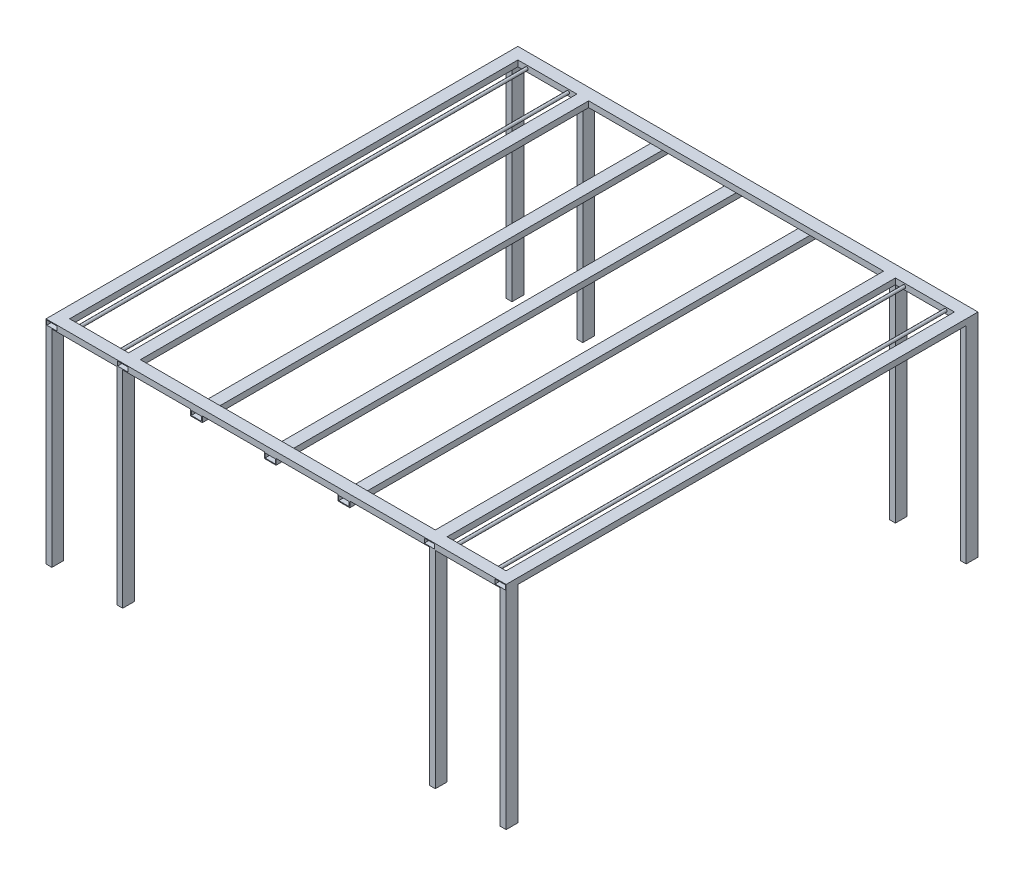
SolidWorks part; units mm, degrees
ref_plane "Front Plane" through (0, 0, 0) normal (0, 0, 1) x (1, 0, 0)
ref_plane "Top Plane" through (0, 0, 0) normal (0, 1, 0) x (1, 0, 0)
ref_plane "Right Plane" through (0, 0, 0) normal (1, 0, 0) x (0, 0, -1)
sketch "Sketch1" plane through (0, 0, 0) normal (0, 0, 1) x (1, 0, 0)
  line L0 (-17.5, 7.5) -> (17.5, 7.5)
  line L1 (-20, 10) -> (20, 10)
  line L2 (-20, 10) -> (-20, -10)
  line L3 (-20, -10) -> (20, -10)
  line L4 (20, 10) -> (20, -10)
  line L5 (-20, 10) -> (20, -10) construction
  line L6 (-20, -10) -> (20, 10) construction
  line L7 (17.5, 7.5) -> (17.5, -7.5)
  line L8 (-17.5, -7.5) -> (17.5, -7.5)
  line L9 (-17.5, 7.5) -> (-17.5, -7.5)
  point P0 (0, 0)
  dimension "D1" = 40
  dimension "D2" = 20
  dimension "D3" = 2.5
extrude "Boss-Extrude1" add sketch "Sketch1" along normal blind 1600
sketch "Sketch2" plane through (20, 0, 0) normal (1, 0, 0) x (0, 0, -1)
  line L0 (-1600, -10) -> (0, -10) construction
  line L1 (-1600, 10) -> (-1560, 10)
  line L2 (-1600, 10) -> (-1600, -10)
  line L3 (-1600, -10) -> (-1560, -10)
  line L4 (-1560, 10) -> (-1560, -10)
  line L5 (-1597.5, 7.5) -> (-1562.5, 7.5)
  line L6 (-1562.5, 7.5) -> (-1562.5, -7.5)
  line L7 (-1597.5, -7.5) -> (-1562.5, -7.5)
  line L8 (-1597.5, 7.5) -> (-1597.5, -7.5)
  line L9 (-2.5, 7.5) -> (-37.5, 7.5)
  line L10 (0, 10) -> (-40, 10)
  line L11 (0, 10) -> (0, -10)
  line L12 (0, -10) -> (-40, -10)
  line L13 (-40, 10) -> (-40, -10)
  line L14 (-37.5, 7.5) -> (-37.5, -7.5)
  line L15 (-2.5, -7.5) -> (-37.5, -7.5)
  line L16 (-2.5, 7.5) -> (-2.5, -7.5)
  dimension "D1" = 2.5
  dimension "D2" = 2.5
  dimension "D3" = 40
extrude "Boss-Extrude3" add sketch "Sketch2" along normal blind 1000
sketch "Sketch3" plane through (0, 0, 1600) normal (0, 0, 1) x (1, 0, 0)
  line L0 (1022.5, 7.5) -> (1057.5, 7.5)
  line L1 (1020, 10) -> (1060, 10)
  line L2 (1020, 10) -> (1020, -10)
  line L3 (1020, -10) -> (1060, -10)
  line L4 (1060, 10) -> (1060, -10)
  line L5 (1057.5, 7.5) -> (1057.5, -7.5)
  line L6 (1022.5, -7.5) -> (1057.5, -7.5)
  line L7 (1022.5, 7.5) -> (1022.5, -7.5)
  dimension "D1" = 40
  dimension "D2" = 2.5
extrude "Boss-Extrude4" add sketch "Sketch3" against normal blind 1600
sketch "Sketch4" plane through (0, -10, 0) normal (0, -1, 0) x (1, 0, 0)
  line L0 (1057.5, 1597.5) -> (1057.5, 1562.5)
  line L1 (1060, 1600) -> (1040, 1600)
  line L2 (1060, 1600) -> (1060, 1560)
  line L3 (1060, 1560) -> (1040, 1560)
  line L4 (1040, 1600) -> (1040, 1560)
  line L5 (1060, 0) -> (1040, 0)
  line L6 (1060, 0) -> (1060, 40)
  line L7 (1060, 40) -> (1040, 40)
  line L8 (1040, 0) -> (1040, 40)
  line L9 (-20, 0) -> (0, 0)
  line L10 (-20, 0) -> (-20, 40)
  line L11 (-20, 40) -> (0, 40)
  line L12 (0, 0) -> (0, 40)
  line L13 (-20, 1600) -> (0, 1600)
  line L14 (-20, 1600) -> (-20, 1560)
  line L15 (-20, 1560) -> (0, 1560)
  line L16 (0, 1600) -> (0, 1560)
  line L17 (1057.5, 1562.5) -> (1042.5, 1562.5)
  line L18 (1042.5, 1597.5) -> (1042.5, 1562.5)
  line L19 (1057.5, 1597.5) -> (1042.5, 1597.5)
  line L20 (1057.5, 2.5) -> (1057.5, 37.5)
  line L21 (1057.5, 37.5) -> (1042.5, 37.5)
  line L22 (1042.5, 2.5) -> (1042.5, 37.5)
  line L23 (1057.5, 2.5) -> (1042.5, 2.5)
  line L24 (-17.5, 2.5) -> (-17.5, 37.5)
  line L25 (-17.5, 37.5) -> (-2.5, 37.5)
  line L26 (-2.5, 2.5) -> (-2.5, 37.5)
  line L27 (-17.5, 2.5) -> (-2.5, 2.5)
  line L28 (-17.5, 1597.5) -> (-17.5, 1562.5)
  line L29 (-17.5, 1562.5) -> (-2.5, 1562.5)
  line L30 (-2.5, 1597.5) -> (-2.5, 1562.5)
  line L31 (-17.5, 1597.5) -> (-2.5, 1597.5)
  dimension "D1" = 20
  dimension "D2" = 20
  dimension "D3" = 20
  dimension "D4" = 20
  dimension "D6" = 40
  dimension "40" = 40
  dimension "D5" = 2.5
extrude "Boss-Extrude5" add sketch "Sketch4" along normal blind 700
sketch "Sketch5" plane through (0, 0, 1600) normal (0, 0, 1) x (1, 0, 0)
  line L0 (0, -10) -> (1040, -10) construction
  line L1 (230, -10) -> (270, -10)
  line L2 (230, -10) -> (230, -30)
  line L3 (230, -30) -> (270, -30)
  line L4 (270, -10) -> (270, -30)
  line L5 (0, -710) -> (0, -10) construction
  line L6 (480, -10) -> (520, -10)
  line L7 (480, -10) -> (480, -30)
  line L8 (480, -30) -> (520, -30)
  line L9 (520, -10) -> (520, -30)
  line L10 (730, -10) -> (770, -10)
  line L11 (730, -10) -> (730, -30)
  line L12 (730, -30) -> (770, -30)
  line L13 (770, -10) -> (770, -30)
  line L14 (232.5, -27.5) -> (267.5, -27.5)
  line L15 (267.5, -12.5) -> (267.5, -27.5)
  line L16 (232.5, -12.5) -> (267.5, -12.5)
  line L17 (232.5, -12.5) -> (232.5, -27.5)
  line L18 (482.5, -27.5) -> (517.5, -27.5)
  line L19 (517.5, -12.5) -> (517.5, -27.5)
  line L20 (482.5, -12.5) -> (517.5, -12.5)
  line L21 (482.5, -12.5) -> (482.5, -27.5)
  line L22 (732.5, -27.5) -> (767.5, -27.5)
  line L23 (767.5, -12.5) -> (767.5, -27.5)
  line L24 (732.5, -12.5) -> (767.5, -12.5)
  line L25 (732.5, -12.5) -> (732.5, -27.5)
  point P16 (500, -10)
  point P17 (500, -30)
  point P18 (250, -30)
  point P19 (750, -30)
  dimension "D1" = 40
  dimension "D2" = 20
  dimension "D3" = 20
  dimension "D4" = 40
  dimension "D5" = 20
  dimension "D6" = 40
  dimension "D7" = 500
  dimension "D8" = 250
  dimension "D9" = 250
  dimension "D10" = 2.5
extrude "Boss-Extrude6" add sketch "Sketch5" against normal blind 1600
sketch "Sketch7" plane through (1060, 0, 0) normal (1, 0, 0) x (0, 0, -1)
  line L0 (-37.5, 7.5) -> (-2.5, 7.5)
  line L1 (-1600, 10) -> (-1560, 10)
  line L2 (-1600, 10) -> (-1600, -10)
  line L3 (-1600, -10) -> (-1560, -10)
  line L4 (-1560, 10) -> (-1560, -10)
  line L5 (-40, -10) -> (0, -10)
  line L6 (-40, -10) -> (-40, 10)
  line L7 (-40, 10) -> (0, 10)
  line L8 (0, -10) -> (0, 10)
  line L9 (-2.5, -7.5) -> (-2.5, 7.5)
  line L10 (-37.5, -7.5) -> (-2.5, -7.5)
  line L11 (-37.5, -7.5) -> (-37.5, 7.5)
  line L12 (-1597.5, 7.5) -> (-1562.5, 7.5)
  line L13 (-1562.5, 7.5) -> (-1562.5, -7.5)
  line L14 (-1597.5, -7.5) -> (-1562.5, -7.5)
  line L15 (-1597.5, 7.5) -> (-1597.5, -7.5)
  dimension "D1" = 2.5
extrude "Boss-Extrude7" add sketch "Sketch7" along normal blind 200
sketch "Sketch10" plane through (-20, 0, 0) normal (-1, 0, 0) x (0, 0, 1)
  line L0 (1562.5, -7.5) -> (1562.5, 7.5)
  line L1 (0, 10) -> (40, 10)
  line L2 (0, 10) -> (0, -10)
  line L3 (0, -10) -> (40, -10)
  line L4 (40, 10) -> (40, -10)
  line L5 (1560, -10) -> (1600, -10)
  line L6 (1560, -10) -> (1560, 10)
  line L7 (1560, 10) -> (1600, 10)
  line L8 (1600, -10) -> (1600, 10)
  line L9 (1562.5, 7.5) -> (1597.5, 7.5)
  line L10 (1597.5, -7.5) -> (1597.5, 7.5)
  line L11 (1562.5, -7.5) -> (1597.5, -7.5)
  line L12 (2.5, -7.5) -> (37.5, -7.5)
  line L13 (37.5, 7.5) -> (37.5, -7.5)
  line L14 (2.5, 7.5) -> (37.5, 7.5)
  line L15 (2.5, 7.5) -> (2.5, -7.5)
  dimension "D1" = 2.5
extrude "Boss-Extrude9" add sketch "Sketch10" along normal blind 200
sketch "Sketch11" plane through (0, 0, 0) normal (0, 0, -1) x (-1, 0, 0)
  line L0 (-1262.5, 7.5) -> (-1297.5, 7.5)
  line L1 (220, 10) -> (260, 10)
  line L2 (220, 10) -> (220, -10)
  line L3 (220, -10) -> (260, -10)
  line L4 (260, 10) -> (260, -10)
  line L5 (-1260, 10) -> (-1300, 10)
  line L6 (-1260, 10) -> (-1260, -10)
  line L7 (-1260, -10) -> (-1300, -10)
  line L8 (-1300, 10) -> (-1300, -10)
  line L9 (-1297.5, 7.5) -> (-1297.5, -7.5)
  line L10 (-1262.5, -7.5) -> (-1297.5, -7.5)
  line L11 (-1262.5, 7.5) -> (-1262.5, -7.5)
  line L12 (222.5, 7.5) -> (257.5, 7.5)
  line L13 (257.5, 7.5) -> (257.5, -7.5)
  line L14 (222.5, -7.5) -> (257.5, -7.5)
  line L15 (222.5, 7.5) -> (222.5, -7.5)
  dimension "D1" = 40
  dimension "D2" = 40
  dimension "D3" = 2.5
extrude "Boss-Extrude10" add sketch "Sketch11" against normal blind 1600
sketch "Sketch12" plane through (0, -10, 0) normal (0, -1, 0) x (1, 0, 0)
  line L0 (-242.5, 2.5) -> (-242.5, 37.5)
  line L1 (1300, 0) -> (1280, 0)
  line L2 (1300, 0) -> (1300, 40)
  line L3 (1300, 40) -> (1280, 40)
  line L4 (1280, 0) -> (1280, 40)
  line L5 (-260, 0) -> (-240, 0)
  line L6 (-260, 0) -> (-260, 40)
  line L7 (-260, 40) -> (-240, 40)
  line L8 (-240, 0) -> (-240, 40)
  line L9 (1300, 1600) -> (1280, 1600)
  line L10 (-260, 1600) -> (-240, 1600)
  line L11 (-260, 1600) -> (-260, 1560)
  line L12 (-260, 1560) -> (-240, 1560)
  line L13 (-240, 1600) -> (-240, 1560)
  line L14 (1300, 1600) -> (1300, 1560)
  line L15 (1300, 1560) -> (1280, 1560)
  line L16 (1280, 1600) -> (1280, 1560)
  line L17 (-257.5, 37.5) -> (-242.5, 37.5)
  line L18 (-257.5, 2.5) -> (-257.5, 37.5)
  line L19 (-257.5, 2.5) -> (-242.5, 2.5)
  line L20 (1282.5, 2.5) -> (1282.5, 37.5)
  line L21 (1297.5, 37.5) -> (1282.5, 37.5)
  line L22 (1297.5, 2.5) -> (1297.5, 37.5)
  line L23 (1297.5, 2.5) -> (1282.5, 2.5)
  line L24 (1282.5, 1597.5) -> (1282.5, 1562.5)
  line L25 (1297.5, 1562.5) -> (1282.5, 1562.5)
  line L26 (1297.5, 1597.5) -> (1297.5, 1562.5)
  line L27 (1297.5, 1597.5) -> (1282.5, 1597.5)
  line L28 (-242.5, 1597.5) -> (-242.5, 1562.5)
  line L29 (-257.5, 1562.5) -> (-242.5, 1562.5)
  line L30 (-257.5, 1597.5) -> (-257.5, 1562.5)
  line L31 (-257.5, 1597.5) -> (-242.5, 1597.5)
  dimension "D1" = 20
  dimension "D2" = 40
  dimension "D3" = 40
  dimension "D4" = 20
  dimension "D5" = 20
  dimension "D6" = 40
  dimension "D7" = 2.5
extrude "Boss-Extrude11" add sketch "Sketch12" along normal blind 700
sketch "Sketch14" plane through (0, 0, 1560) normal (0, 0, -1) x (-1, 0, 0)
  line L0 (-520, 10) -> (-520, -10)
  line L1 (-1020, 10) -> (-20, 10) construction
  line L2 (-1260, 10) -> (-1060, 10) construction
  circle A0 centre (-1230, 0) radius 5
  circle A1 centre (-1090, 0) radius 5
  circle A2 centre (50, 0) radius 5
  circle A3 centre (190, 0) radius 5
  point P11 (-1160, 10)
  dimension "D1" = 10
  dimension "D2" = 10
  dimension "D3" = 140
  dimension "D4" = 70
extrude "Boss-Extrude13" add sketch "Sketch14" along normal blind 1550 contours A0 | A1 | A2 | A3
